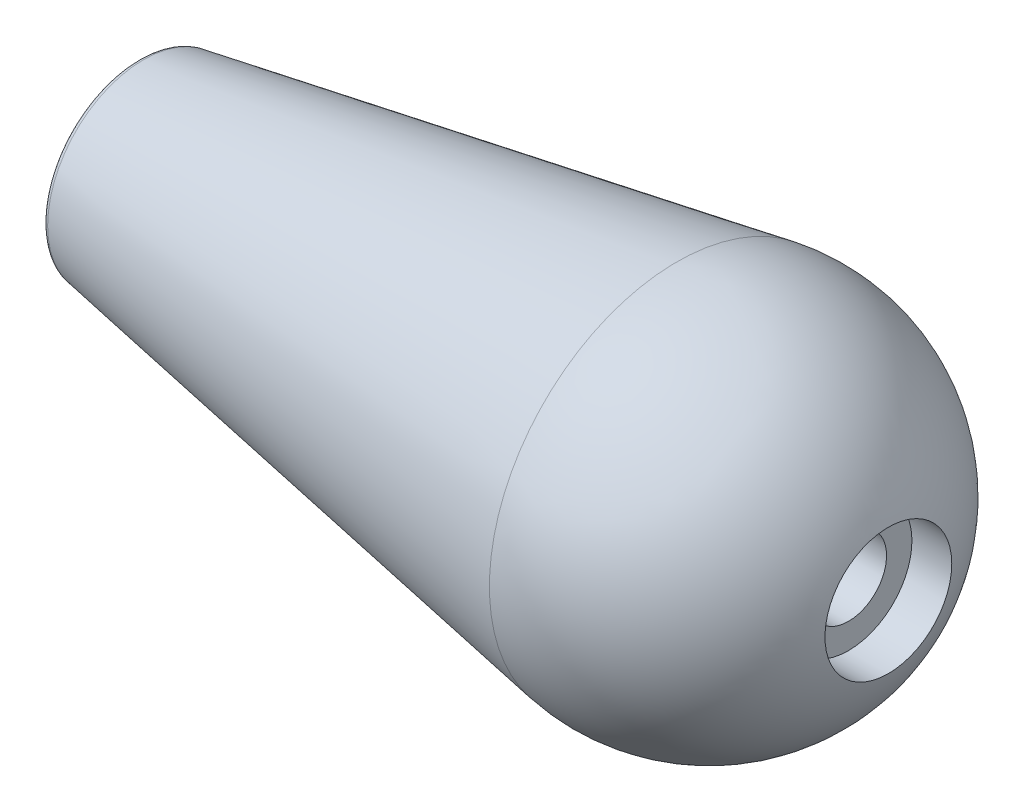
SolidWorks part; units mm, degrees
ref_plane "Front Plane" through (0, 0, 0) normal (0, 0, 1) x (1, 0, 0)
ref_plane "Top Plane" through (0, 0, 0) normal (0, 1, 0) x (1, 0, 0)
ref_plane "Right Plane" through (0, 0, 0) normal (1, 0, 0) x (0, 0, -1)
sketch "Sketch1" plane through (0, 0, 0) normal (0, 1, 0) x (1, 0, 0)
  line L0 (0, 0) -> (120, 0)
  line L1 (0, 0) -> (0, 15)
  line L2 (0, 15) -> (84.928, 29.5681)
  arc A0 (120, 0) -> (84.928, 29.5681) centre (90, 0) ccw
  dimension "D2" = 30
  dimension "D1" = 120
  dimension "D3" = 15
revolve "Revolve1" add sketch "Sketch1" angle 360 about L0
sketch "Sketch2" plane through (0, 0, 0) normal (0, 0, 1) x (1, 0, 0)
  line L0 (0, 0) -> (120, 0)
  line L1 (120, 0) -> (120, 10)
  line L2 (120, 10) -> (112, 10)
  line L3 (112, 10) -> (112, 6)
  line L4 (0, 0) -> (0, 10)
  line L5 (0, 15) -> (0, -15) construction
  line L6 (0, 10) -> (8, 10)
  line L7 (8, 10) -> (8, 6)
  line L8 (8, 6) -> (112, 6)
  arc A0 (84.928, -29.5681) -> (84.928, 29.5681) centre (90, 0) ccw construction
  dimension "D1" = 10
  dimension "D2" = 8
  dimension "D3" = 10
  dimension "D4" = 8
  dimension "D5" = 6
revolve "Cut-Revolve2" cut sketch "Sketch2" angle 360 about L0
fillet "Fillet1" radius 1 1 edges at (0, 0, 15)
